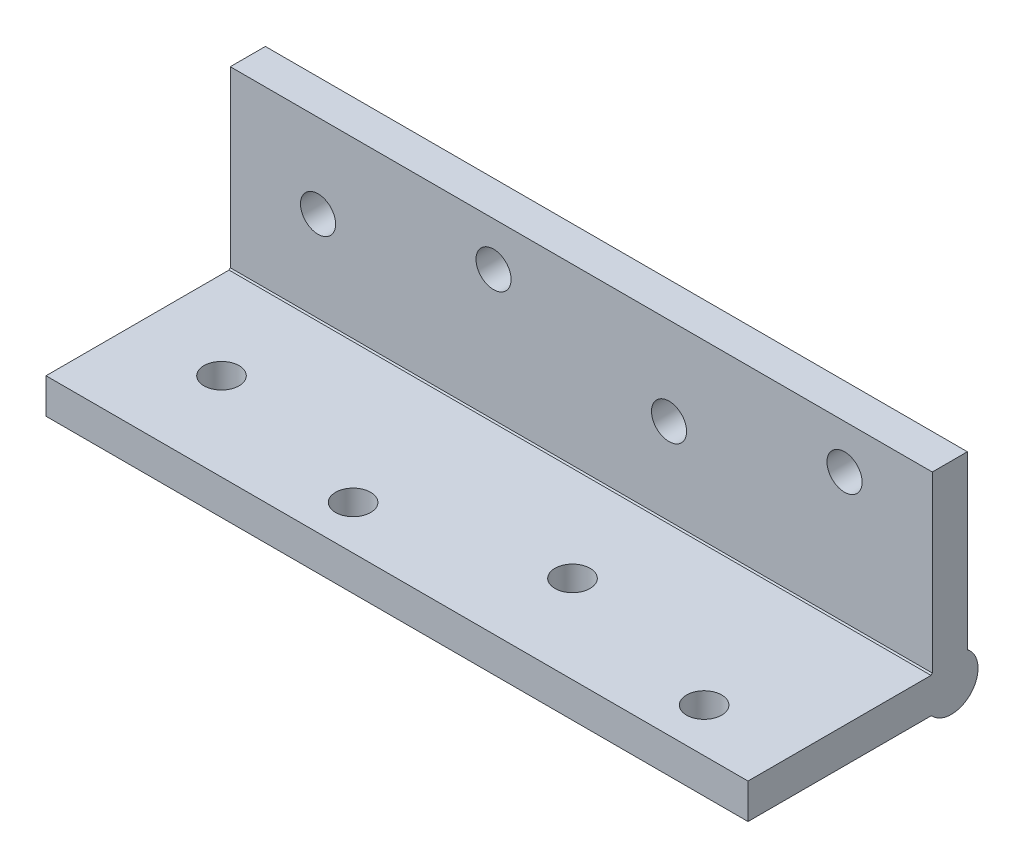
SolidWorks part; units mm, degrees
ref_plane "Front Plane" through (0, 0, 0) normal (0, 0, 1) x (1, 0, 0)
ref_plane "Top Plane" through (0, 0, 0) normal (0, 1, 0) x (1, 0, 0)
ref_plane "Right Plane" through (0, 0, 0) normal (1, 0, 0) x (0, 0, -1)
sketch "Sketch1" plane through (0, 0, 0) normal (0, 1, 0) x (1, 0, 0)
  line L1 (-40, 12.5) -> (40, 12.5)
  line L2 (-40, 12.5) -> (-40, -12.5)
  line L3 (-40, -12.5) -> (40, -12.5)
  line L4 (40, 12.5) -> (40, -12.5)
  line L5 (-40, 12.5) -> (40, -12.5) construction
  line L6 (-40, -12.5) -> (40, 12.5) construction
  point P0 (0, 0)
  dimension "D1" = 25
  dimension "D2" = 80
extrude "Boss-Extrude1" add sketch "Sketch1" along normal blind 4
sketch "Sketch2" plane through (0, 4, 0) normal (0, 1, 0) x (1, 0, 0)
  line L0 (40, -12.5) -> (40, 12.5) construction
  line L1 (-40, 12.5) -> (40, 12.5)
  line L2 (-40, 12.5) -> (-40, 8.5)
  line L3 (-40, 8.5) -> (40, 8.5)
  line L4 (40, 12.5) -> (40, 8.5)
  dimension "D1" = 4
extrude "Boss-Extrude2" add sketch "Sketch2" along normal blind 20
sketch "Sketch3" plane through (-40, 0, 0) normal (-1, 0, 0) x (0, 0, 1)
  circle A0 centre (-10.6734, 2.0282) radius 3.0428
extrude "Boss-Extrude3" add sketch "Sketch3" against normal blind 80
sketch "Sketch4" plane through (0, 0, -12.5) normal (0, 0, -1) x (-1, 0, 0)
  line L0 (-40, 4.4617) -> (40, 4.4617) construction
  line L1 (-40, 24) -> (40, 24) construction
  line L2 (40, 24) -> (40, 4.4617) construction
  line L3 (-40, 24) -> (-40, 4.4617) construction
  circle A0 centre (30, 14.4617) radius 2
  circle A1 centre (-10, 14) radius 2
  circle A2 centre (10, 19) radius 2
  circle A3 centre (-30, 19) radius 2
  dimension "D2" = 4
  dimension "D3" = 4
  dimension "D4" = 4
  dimension "D8" = 4
  dimension "D1" = 10
  dimension "D5" = 5
  dimension "D6" = 5
  dimension "D7" = 10
  dimension "D9" = 10
  dimension "D10" = 30
  dimension "D11" = 30
  dimension "D12" = 10
extrude "Cut-Extrude1" cut sketch "Sketch4" against normal blind 80
sketch "Sketch5" plane through (0, 0, 0) normal (0, -1, 0) x (1, 0, 0)
  line L0 (-40, -8.4052) -> (-40, 12.5) construction
  line L1 (40, 12.5) -> (40, -8.4052) construction
  line L2 (-40, 12.5) -> (40, 12.5) construction
  circle A0 centre (-30, 2.5) radius 2
  circle A1 centre (-10, 7.5) radius 2
  circle A2 centre (10, 2.5) radius 2
  circle A3 centre (30, 7.5) radius 2
  dimension "D1" = 4
  dimension "D2" = 4
  dimension "D3" = 4
  dimension "D4" = 4
  dimension "D5" = 10
  dimension "D6" = 30
  dimension "D7" = 30
  dimension "D8" = 10
  dimension "D9" = 5
  dimension "D10" = 5
  dimension "D11" = 10
  dimension "D12" = 10
extrude "Cut-Extrude2" cut sketch "Sketch5" against normal blind 80
